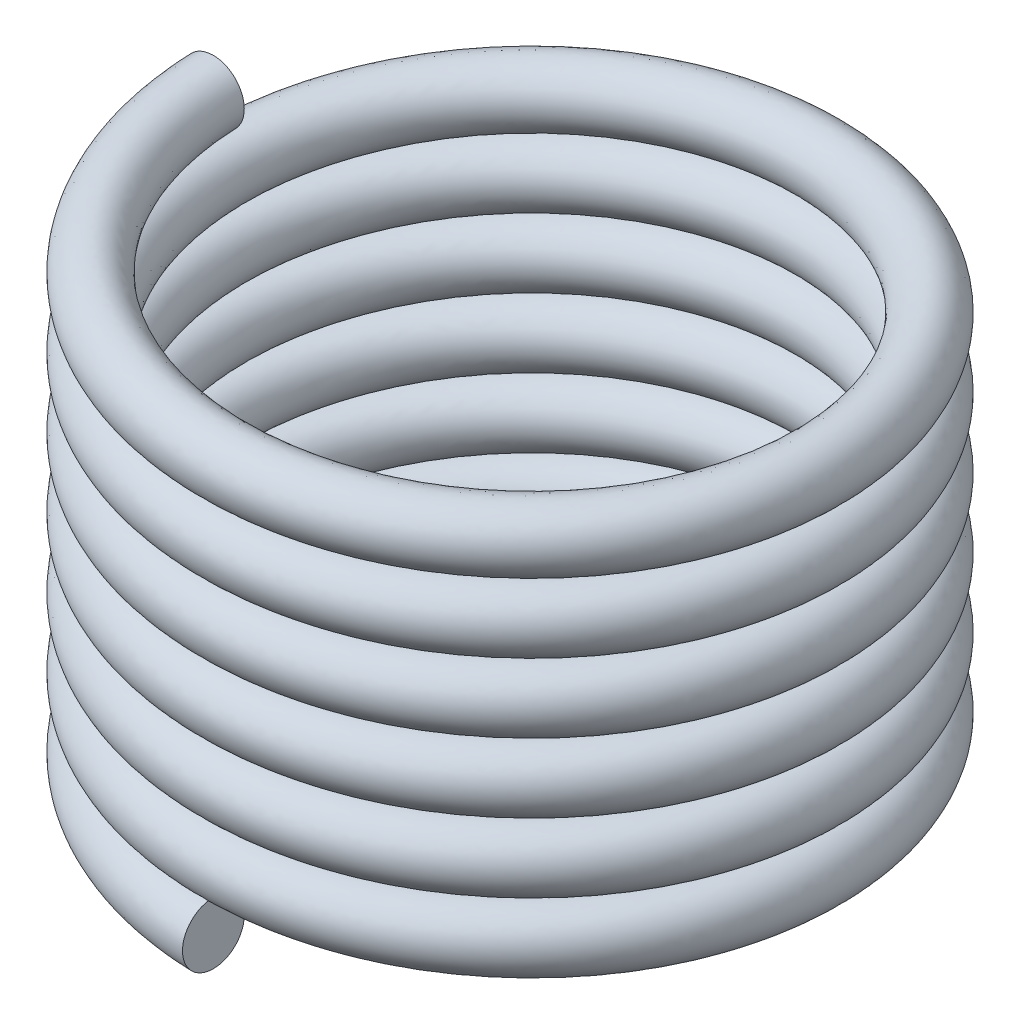
SolidWorks part; units mm, degrees
material "1.4016 (X6Cr17)"
ref_plane "Płaszczyzna przednia" through (0, 0, 0) normal (0, 0, 1) x (1, 0, 0)
ref_plane "Płaszczyzna górna" through (0, 0, 0) normal (0, 1, 0) x (1, 0, 0)
ref_plane "Płaszczyzna prawa" through (0, 0, 0) normal (1, 0, 0) x (0, 0, -1)
sketch "Szkic1" plane through (0, 0, 0) normal (1, 0, 0) x (0, 0, -1)
  circle A0 centre (-12, 0) radius 1.25
  dimension "D1" = 2.5
  dimension "D2" = 12
sketch "Szkic3" plane through (0, 0, 0) normal (0, 1, 0) x (1, 0, 0)
  circle A0 centre (0, 0) radius 12
curve "Helisa/Spirala1" pitch 2.8 height 17.5 turns 6.25
sweep "Wyciągnięcie po ścieżce1" add profiles "Szkic1" path "Helisa/Spirala1"
sketch "Szkic4" plane through (0, 0, 0) normal (0, 0, 1) x (1, 0, 0)
  line L0 (0, 0) -> (0, 7.3891) construction
